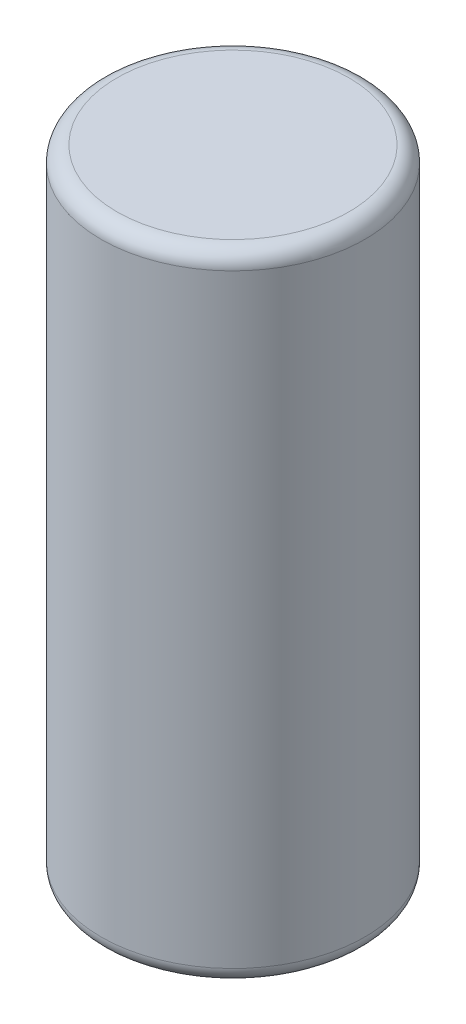
SolidWorks part; units mm, degrees
material "Alloy Steel"
ref_plane "Front Plane" through (0, 0, 0) normal (0, 0, 1) x (1, 0, 0)
ref_plane "Top Plane" through (0, 0, 0) normal (0, 1, 0) x (1, 0, 0)
ref_plane "Right Plane" through (0, 0, 0) normal (1, 0, 0) x (0, 0, -1)
sketch "Sketch1" plane through (0, 0, 0) normal (0, 1, 0) x (1, 0, 0)
  circle A0 centre (0, 0) radius 4.15
  dimension "D1" = 8.3
extrude "Boss-Extrude1" add sketch "Sketch1" along normal blind 20
fillet "Fillet1" radius 0.5 2 edges at (0, 0, 4.15) (0, 20, 4.15)
